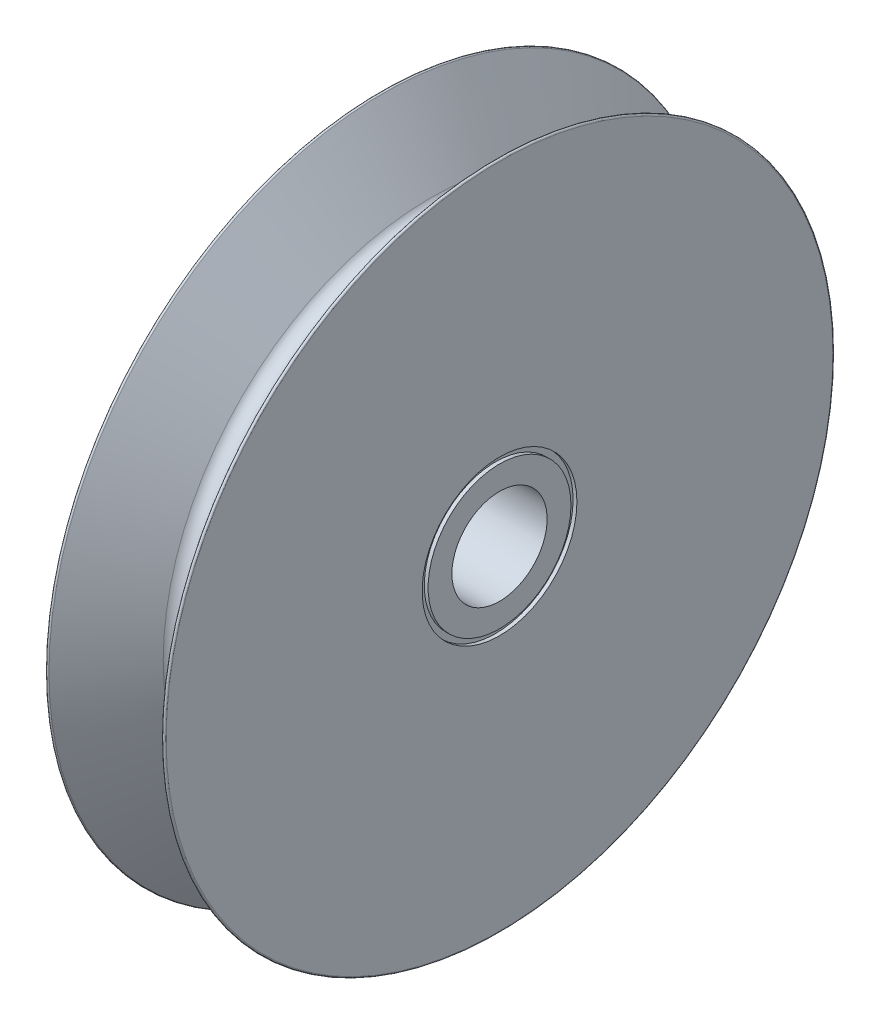
SolidWorks part; units mm, degrees
material "Plain Carbon Steel"
ref_plane "Front Plane" through (0, 0, 0) normal (0, 0, 1) x (1, 0, 0)
ref_plane "Top Plane" through (0, 0, 0) normal (0, 1, 0) x (1, 0, 0)
ref_plane "Right Plane" through (0, 0, 0) normal (1, 0, 0) x (0, 0, -1)
sketch "Sketch1" plane through (0, 0, 0) normal (0, 0, 1) x (1, 0, 0)
  line L0 (0, 0) -> (7.9375, 0) construction
  line L1 (0, 3.175) -> (7.9375, 3.175)
  line L2 (7.9375, 3.175) -> (7.9375, 22.225)
  line L3 (7.7556, 22.2823) -> (4.619, 17.8011)
  line L4 (3.3185, 17.8011) -> (0.1819, 22.2823)
  line L5 (0, 22.225) -> (0, 3.175)
  line L6 (0, 3.175) -> (0, 0) construction
  line L7 (7.9375, 3.175) -> (7.9375, 0) construction
  line L8 (0, 17.4625) -> (7.9375, 17.4625) construction
  arc A0 (4.619, 17.8011) -> (3.3185, 17.8011) centre (3.9688, 18.2562) cw
  arc A1 (7.9375, 22.225) -> (7.7556, 22.2823) centre (7.8375, 22.225) ccw
  arc A2 (0.1819, 22.2823) -> (0, 22.225) centre (0.1, 22.225) ccw
  dimension "D1" = 0.7937
  dimension "D3" = 0.1
  dimension "D2" = 6.35
  dimension "D4" = 44.45
  dimension "D5" = 17.4625
  dimension "D6" = 7.9375
revolve "Revolve1" add sketch "Sketch1" angle 360 about L0
sketch "Sketch4" plane through (7.9375, 0, 0) normal (1, 0, 0) x (0, 0, -1)
  line L0 (0, 3.175) -> (0, 4.7625) construction
  line L1 (0, 4.7625) -> (0, 5.1594) construction
  line L2 (0, 5.1594) -> (0, 22.225) construction
  line L3 (0, 3.175) -> (0, 0) construction
  circle A0 centre (0, 0) radius 4.7625
  circle A1 centre (0, 0) radius 5.1594
  circle A2 centre (0, 0) radius 3.175 construction
  circle A3 centre (0, 0) radius 22.225 construction
  dimension "D1" = 1.5875
  dimension "D2" = 0.3969
extrude "Cut-Extrude1" cut sketch "Sketch4" against normal blind 0.254
sketch "Sketch5" plane through (0, 0, 0) normal (-1, 0, 0) x (0, 0, 1)
  line L0 (0, 2.3813) -> (0, 4.7625) construction
  line L1 (0, 4.7625) -> (0, 5.1594) construction
  line L2 (0, 5.1594) -> (0, 6.35) construction
  line L3 (0, 2.3813) -> (0, 0) construction
  circle A0 centre (0, 0) radius 4.7625
  circle A1 centre (0, 0) radius 5.1594
  circle A4 centre (0, 0) radius 4.7625 construction
  circle A5 centre (0, 0) radius 5.1594 construction
extrude "Cut-Extrude2" cut sketch "Sketch5" against normal blind 0.254
